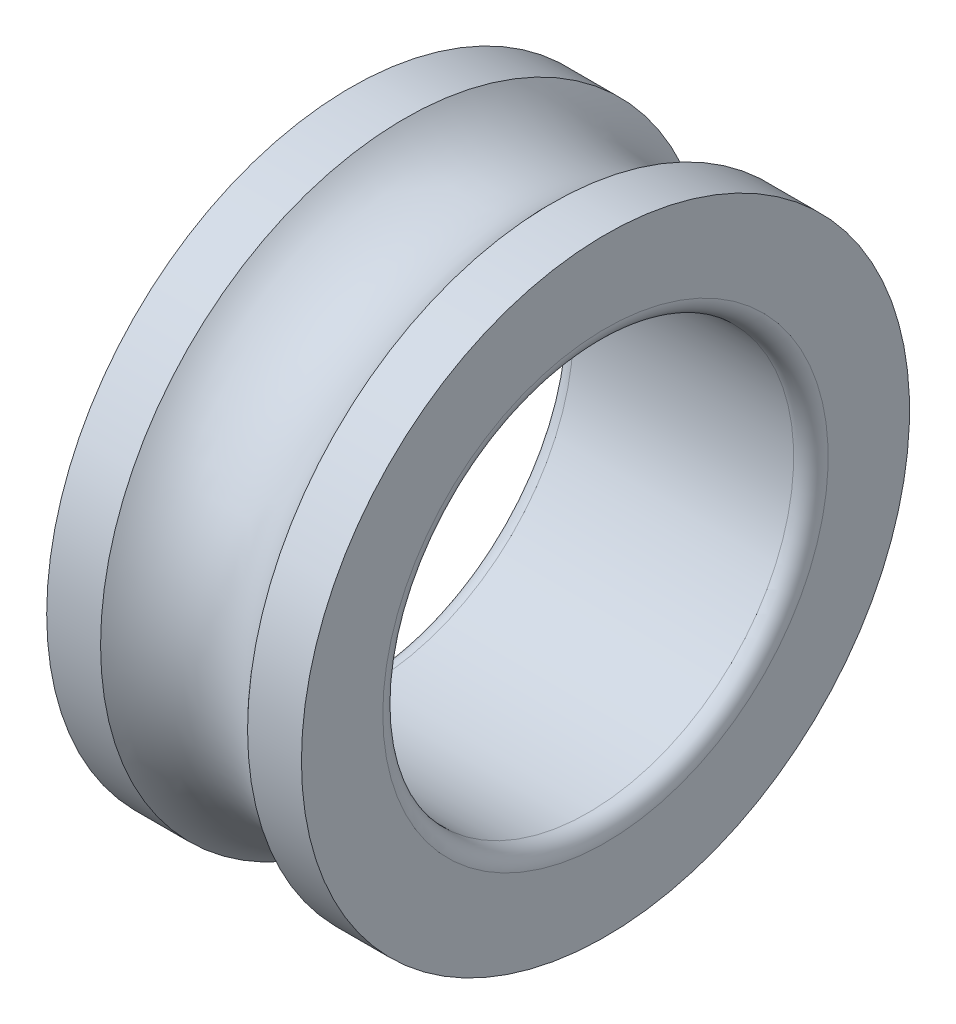
SolidWorks part; units mm, degrees
ref_plane "Front Plane" through (0, 0, 0) normal (0, 0, 1) x (1, 0, 0)
ref_plane "Top Plane" through (0, 0, 0) normal (0, 1, 0) x (1, 0, 0)
ref_plane "Right Plane" through (0, 0, 0) normal (1, 0, 0) x (0, 0, -1)
sketch "Sketch1" plane through (0, 0, 0) normal (0, 0, 1) x (1, 0, 0)
  line L0 (-38.3579, 0) -> (38.3579, 0) construction
  line L1 (8.9443, 37) -> (15.5, 37)
  line L2 (-15.5, 37) -> (-8.9443, 37)
  line L3 (-15.5, 37) -> (-15.5, 27.1)
  line L4 (-13.4, 25) -> (13.4, 25)
  line L5 (15.5, 37) -> (15.5, 27.1)
  line L6 (-15.5, 37) -> (15.5, 25) construction
  line L7 (-15.5, 25) -> (15.5, 37) construction
  arc A0 (8.9443, 37) -> (-8.9443, 37) centre (0, 45) cw
  arc A1 (13.4, 25) -> (15.5, 27.1) centre (13.4, 27.1) ccw
  arc A2 (-15.5, 27.1) -> (-13.4, 25) centre (-13.4, 27.1) ccw
  point P0 (0, 31)
  point P4 (0, 0)
  dimension "D5" = 12
  dimension "D4" = 2.1
  dimension "D1" = 31
  dimension "D2" = 37
  dimension "D3" = 25
revolve "Revolve1" add sketch "Sketch1" angle 360 about L0
